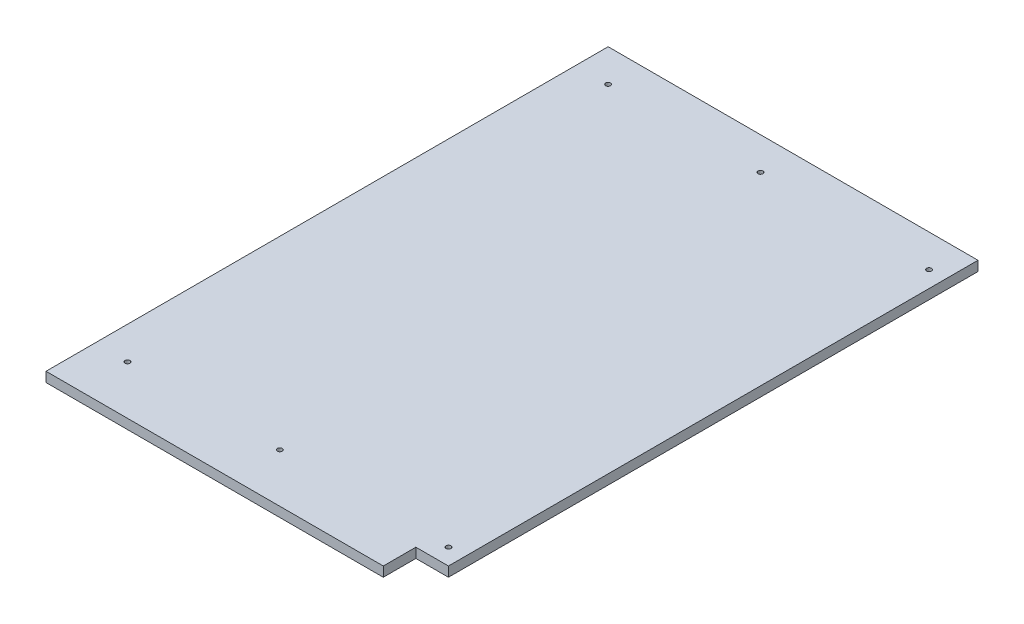
SolidWorks part; units mm, degrees
ref_plane "前视基准面" through (0, 0, 0) normal (0, 0, 1) x (1, 0, 0)
ref_plane "上视基准面" through (0, 0, 0) normal (0, 1, 0) x (1, 0, 0)
ref_plane "右视基准面" through (0, 0, 0) normal (1, 0, 0) x (0, 0, -1)
sketch "草图1" plane through (0, 0, 0) normal (0, 1, 0) x (1, 0, 0)
  line L0 (-112.725, 93.5) -> (114.275, 93.5) construction
  line L1 (-112.725, 113.5) -> (114.275, 113.5)
  line L2 (-112.725, 113.5) -> (-112.725, -231.5)
  line L3 (-112.725, -231.5) -> (94.275, -231.5)
  line L4 (114.275, 113.5) -> (114.275, -211.5)
  line L5 (-112.725, -201.5) -> (114.275, -201.5) construction
  line L8 (94.275, -231.5) -> (94.275, -211.5)
  line L9 (94.275, -211.5) -> (114.275, -211.5)
  circle A0 centre (-92.725, 93.5) radius 1.5
  circle A1 centre (104.275, 93.5) radius 1.5
  circle A2 centre (0.775, 93.5) radius 1.5
  circle A3 centre (-92.725, -201.5) radius 1.5
  circle A4 centre (0.775, -201.5) radius 1.5
  circle A5 centre (104.275, -201.5) radius 1.5
  dimension "D7" = 3
  dimension "D9" = 3
  dimension "D11" = 3
  dimension "D12" = 3
  dimension "D13" = 3
  dimension "D14" = 3
  dimension "D2" = 345
  dimension "D3" = 112.725
  dimension "D4" = 113.5
  dimension "D5" = 20
  dimension "D6" = 30
  dimension "D8" = 20
  dimension "D10" = 10
  dimension "D15" = 227
  dimension "D16" = 20
  dimension "D17" = 10
  dimension "D18" = 20
extrude "凸台-拉伸1" add sketch "草图1" along normal blind 6
